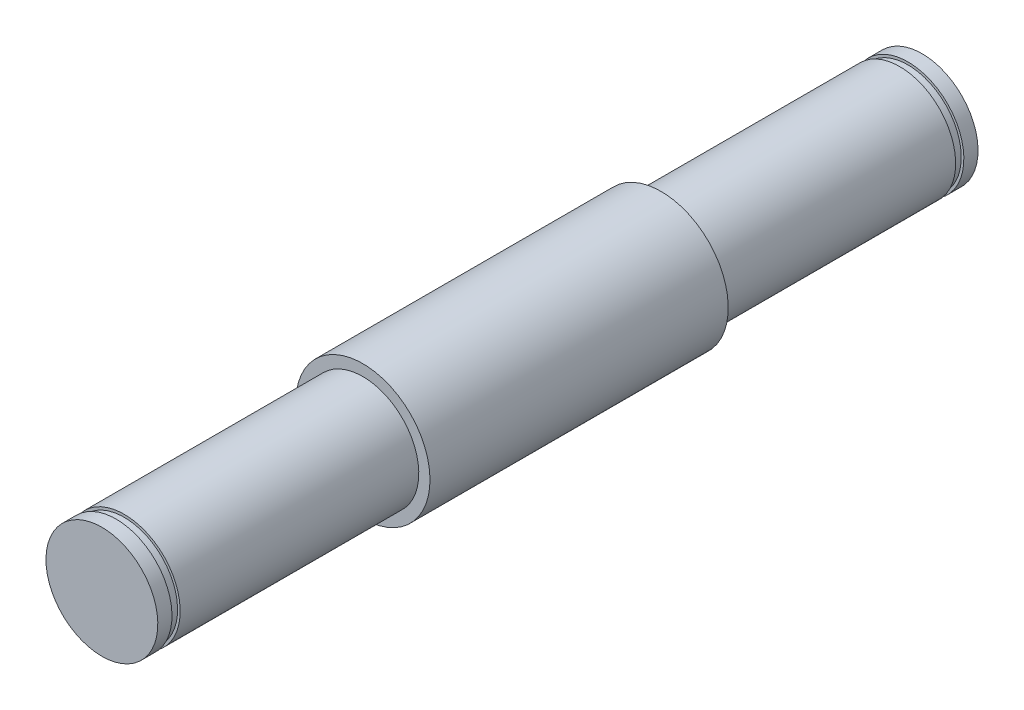
SolidWorks part; units mm, degrees
ref_plane "Płaszczyzna przednia" through (0, 0, 0) normal (0, 0, 1) x (1, 0, 0)
ref_plane "Płaszczyzna górna" through (0, 0, 0) normal (0, 1, 0) x (1, 0, 0)
ref_plane "Płaszczyzna prawa" through (0, 0, 0) normal (1, 0, 0) x (0, 0, -1)
sketch "Szkic1" plane through (0, 0, 0) normal (1, 0, 0) x (0, 0, -1)
  line L0 (-55, 0) -> (55, 0)
  line L1 (55, 0) -> (55, -7.5)
  line L2 (55, -7.5) -> (53.1, -7.5)
  line L3 (53.1, -7.5) -> (53.1, -7.15)
  line L4 (53.1, -7.15) -> (52, -7.15)
  line L5 (52, -7.15) -> (52, -7.5)
  line L6 (52, -7.5) -> (20, -7.5)
  line L7 (20, -7.5) -> (20, -9)
  line L8 (20, -9) -> (-20, -9)
  line L9 (-20, -9) -> (-20, -7.5)
  line L10 (-20, -7.5) -> (-52, -7.5)
  line L11 (-52, -7.5) -> (-52, -7.15)
  line L12 (-52, -7.15) -> (-53.1, -7.15)
  line L13 (-53.1, -7.15) -> (-53.1, -7.5)
  line L14 (-53.1, -7.5) -> (-55, -7.5)
  line L15 (-55, -7.5) -> (-55, 0)
  point P3 (-52.55, -7.15)
  point P18 (-55, -3.75)
  point P19 (0, 0)
  point P22 (52.55, -7.15)
  dimension "D1" = 40
  dimension "D2" = 35
  dimension "D3" = 7.5
  dimension "D4" = 7.15
  dimension "D5" = 1.1
  dimension "D6" = 1.9
  dimension "D7" = 9
  dimension "D8" = 35
  dimension "D9" = 1.9
  dimension "D10" = 1.1
  dimension "D11" = 7.15
revolve "Obrót1" add sketch "Szkic1" angle 360 about L0
